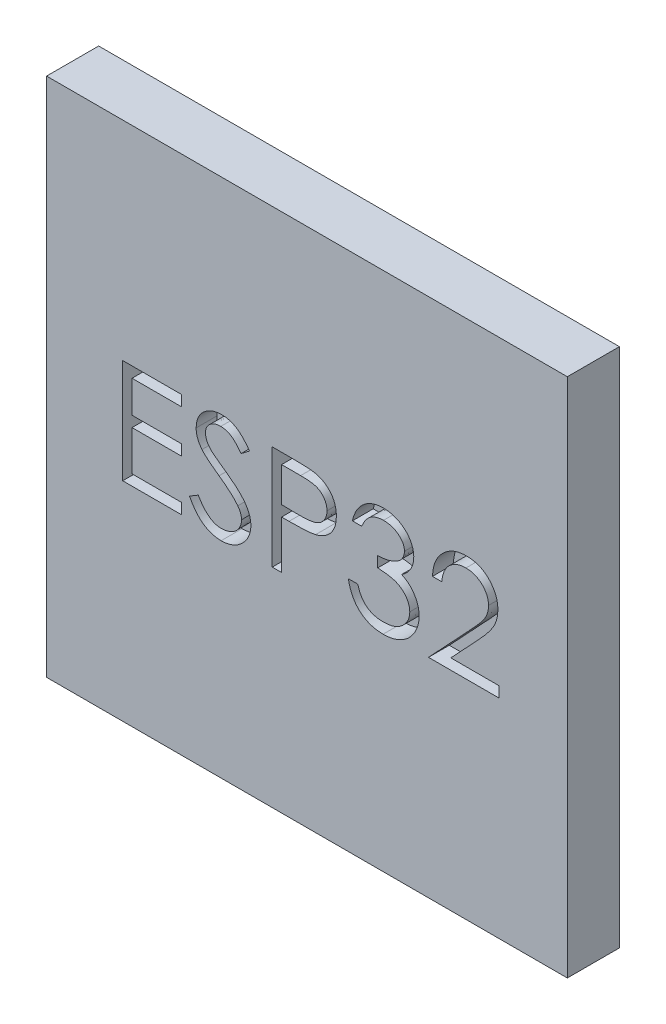
SolidWorks part; units mm, degrees
ref_plane "Front Plane" through (0, 0, 0) normal (0, 0, 1) x (1, 0, 0)
ref_plane "Top Plane" through (0, 0, 0) normal (0, 1, 0) x (1, 0, 0)
ref_plane "Right Plane" through (0, 0, 0) normal (1, 0, 0) x (0, 0, -1)
sketch "Sketch1" plane through (0, 0, 0) normal (0, 0, 1) x (1, 0, 0)
  line L1 (-25, 25) -> (25, 25)
  line L2 (-25, 25) -> (-25, -25)
  line L3 (-25, -25) -> (25, -25)
  line L4 (25, 25) -> (25, -25)
  line L5 (-25, 25) -> (25, -25) construction
  line L6 (-25, -25) -> (25, 25) construction
  point P0 (0, 0)
  dimension "D1" = 50
  dimension "D2" = 50
extrude "Boss-Extrude1" add sketch "Sketch1" along normal blind 5
sketch "Sketch2" plane through (0, 0, 5) normal (0, 0, 1) x (1, 0, 0)
  line L0 (-25, -5) -> (25, -5) construction
  line L1 (-25, 25) -> (-25, -25) construction
  line L2 (25, -25) -> (25, 25) construction
  text T0 "ESP32" font "Century Gothic" height 10
  dimension "D1" = 5
extrude "Cut-Extrude1" cut sketch "Sketch2" against normal blind 2
